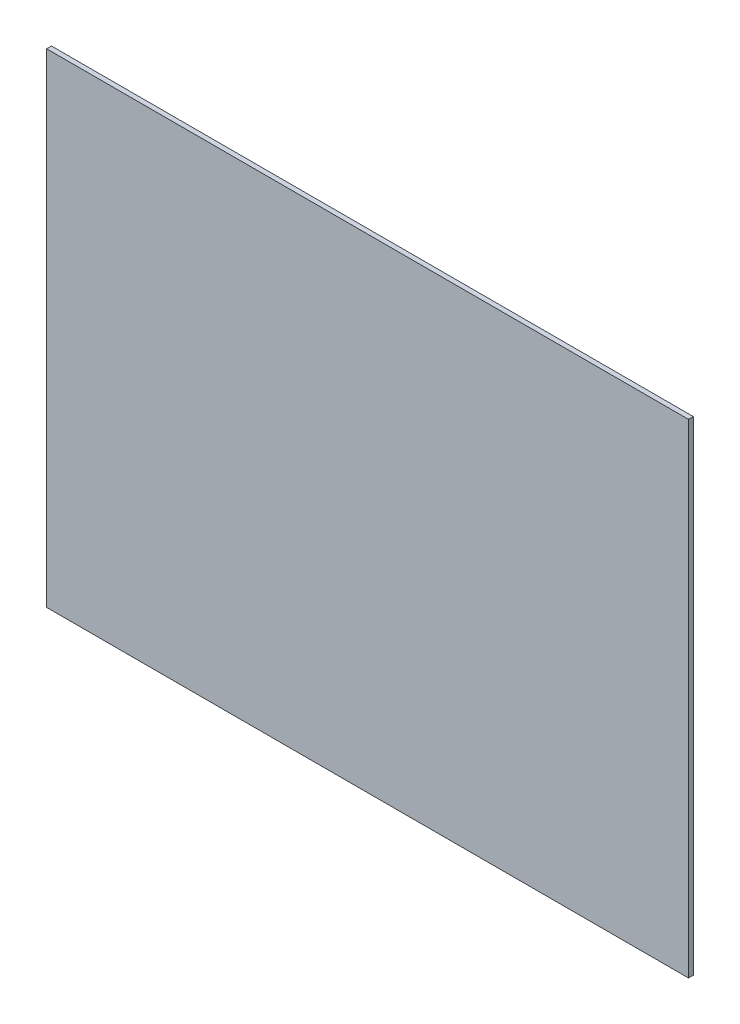
SolidWorks part; units mm, degrees
ref_plane "Alzado" through (0, 0, 0) normal (0, 0, 1) x (1, 0, 0)
ref_plane "Planta" through (0, 0, 0) normal (0, 1, 0) x (1, 0, 0)
ref_plane "Vista lateral" through (0, 0, 0) normal (1, 0, 0) x (0, 0, -1)
sketch "Croquis1" plane through (0, 0, 0) normal (0, 0, 1) x (1, 0, 0)
  line L1 (-199, 150) -> (199, 150)
  line L2 (-199, 150) -> (-199, -150)
  line L3 (-199, -150) -> (199, -150)
  line L4 (199, 150) -> (199, -150)
  line L5 (-199, 150) -> (199, -150) construction
  line L6 (-199, -150) -> (199, 150) construction
  point P0 (0, 0)
  dimension "D1" = 300
  dimension "D2" = 398
extrude "Saliente-Extruir1" add sketch "Croquis1" along normal blind 3
sketch "Sketch1" plane through (0, 0, 3) normal (0, 0, 1) x (1, 0, 0)
  line L1 (-75.5042, 46.5362) -> (55.0269, 46.5362)
  line L2 (-75.5042, 46.5362) -> (-75.5042, 7.9656)
  line L3 (-75.5042, 7.9656) -> (55.0269, 7.9656)
  line L4 (55.0269, 46.5362) -> (55.0269, 7.9656)
